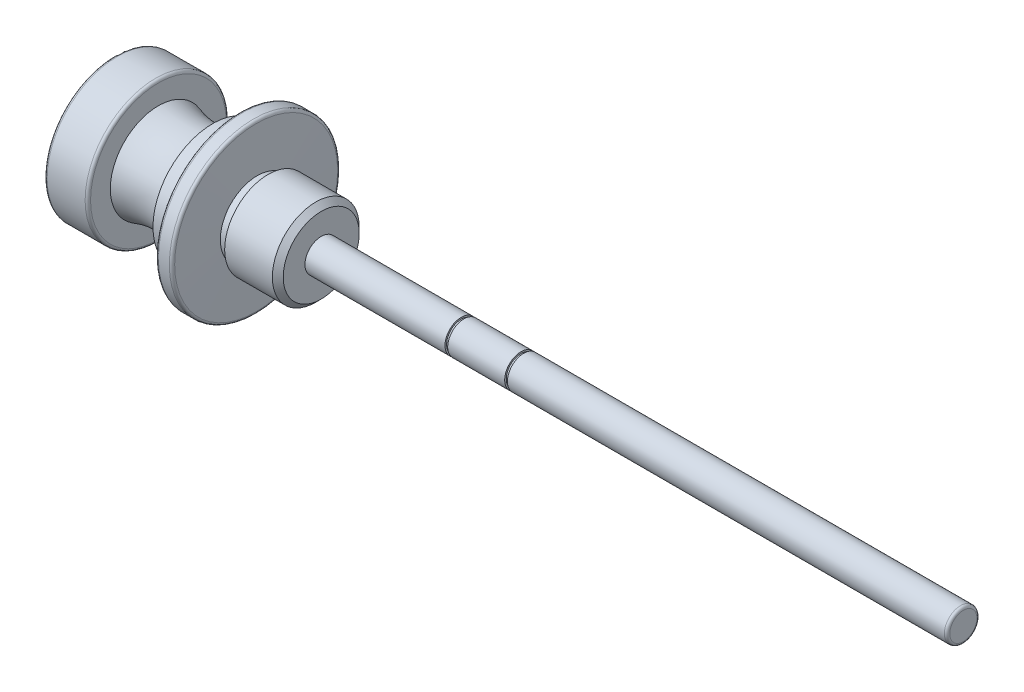
SolidWorks part; units mm, degrees
ref_plane "前视基准面" through (0, 0, 0) normal (0, 0, 1) x (1, 0, 0)
ref_plane "上视基准面" through (0, 0, 0) normal (0, 1, 0) x (1, 0, 0)
ref_plane "右视基准面" through (0, 0, 0) normal (1, 0, 0) x (0, 0, -1)
other "Configuration Table"
sketch "草图1" plane through (0, 0, 0) normal (0, 0, 1) x (1, 0, 0)
  line L0 (0, 0) -> (46.2635, 0) construction
  line L1 (0, 8.8579) -> (0, 11)
  line L2 (0, 11) -> (5, 11)
  line L3 (5, 11) -> (5, 15.5)
  line L4 (5, 15.5) -> (8, 15.5)
  line L5 (8, 15.5) -> (8.2093, 6.8)
  line L6 (8.2093, 6.8) -> (10.2093, 6.8)
  line L7 (10.2093, 6.8) -> (10.2093, 8)
  line L8 (10.2093, 8) -> (20, 8)
  line L9 (20, 8) -> (20, 3)
  line L10 (0, 0) -> (20, 0)
  line L11 (8.3007, 3) -> (138.3007, 3)
  line L12 (138.3007, 3) -> (138.3007, 0)
  line L13 (138.3007, 0) -> (20, 0)
  line L14 (0, 0) -> (-10, 0)
  line L15 (-10, 8.8579) -> (-10, 13)
  line L16 (-10, 13) -> (-18, 13)
  line L17 (-18, 13) -> (-18, 2)
  line L18 (-18, 0) -> (-10, 0)
  line L19 (-5, 0) -> (-5, 15.2334) construction
  line L20 (-18, 0) -> (-20, 0)
  arc A0 (-18, 2) -> (-20, 0) centre (-18, 0) ccw
  arc A1 (-10, 8.8579) -> (0, 8.8579) centre (-5, 23) ccw
  point P24 (-5, 8)
  dimension "D1" = 11
  dimension "D11" = 8
  dimension "D12" = 4
  dimension "D16" = 30
  dimension "D2" = 5
  dimension "D3" = 4.5
  dimension "D4" = 3
  dimension "D5" = 8
  dimension "D6" = 2
  dimension "D7" = 1.2
  dimension "D8" = 9.7907
  dimension "D9" = 3
  dimension "D10" = 130
  dimension "D13" = 8
  dimension "D14" = 10
  dimension "D15" = 13
revolve "旋转1" add sketch "草图1" angle 360 about L0
chamfer "倒角1" distance 1 angle 45 1 edges at (20, 0, 8)
thread "螺纹线1" [suppressed] pitch 0.3175 start angle 0, offset 0, length 10, pitch 0.3175, diameter 16
ref_plane "基准面1" through (10.2093, 0, -8) normal (0, -1, 0) x (0, 0, -1)
sketch "螺纹线轮廓1" plane through (10.2093, 0, -8) normal (0, -1, 0) x (0, 0, -1)
  line L0 (0, 0) -> (0, 0.3175) construction
  line L11 (0, 0) -> (0, 0.2778)
  line L12 (0, 0.2778) -> (-0.1719, 0.1786)
  line L13 (-0.1719, 0.1786) -> (-0.1719, 0.0992)
  line L15 (-0.1719, 0.0992) -> (0, 0)
  line L17 (-0.1719, 0.1389) -> (0, 0.1389) construction
  point P2 (0, 0)
  dimension "Pitch" = 0.3175
  dimension "Profile_Angle" = 60
  dimension "Profile_Land" = 0.0794
  dimension "Profile_Height" = 0.1719
ref_plane "基准面2" through (57.3007, 0, 0) normal (1, 0, 0) x (0, 0, -1)
sketch "草图2" plane through (57.3007, 0, 0) normal (1, 0, 0) x (0, 0, -1)
  circle A0 centre (0, 0) radius 3 construction
  circle A1 centre (0, 0) radius 3
  circle A2 centre (0, 0) radius 2.7
  dimension "D1" = 0.3
extrude "切除-拉伸1" cut sketch "草图2" against normal blind 0.5 contours A1 A2
ref_plane "基准面3" through (46.3007, 0, 0) normal (1, 0, 0) x (0, 0, -1)
sketch "草图3" plane through (46.3007, 0, 0) normal (1, 0, 0) x (0, 0, -1)
  circle A0 centre (0, 0) radius 3 construction
  circle A1 centre (0, 0) radius 3
  circle A2 centre (0, 0) radius 2.7
  dimension "D1" = 0.3
extrude "切除-拉伸2" cut sketch "草图3" against normal blind 0.5
fillet "圆角1" radius 0.5 5 edges at (138.3007, 0, 3) (8, 0, 15.5) (5, 0, 15.5) (-10, 0, 13) (-18, 0, 13)
thread "螺纹线2" [suppressed] pitch 0.3175 start angle 0, offset 0, length 8, pitch 0.3175, diameter 26
ref_plane "基准面4" through (-17.5, 0, -13) normal (0, -1, 0) x (0, 0, -1)
sketch "螺纹线轮廓2" plane through (-17.5, 0, -13) normal (0, -1, 0) x (0, 0, -1)
  line L0 (0, 0) -> (0, 0.3175) construction
  line L11 (0, 0) -> (0, 0.2778)
  line L12 (0, 0.2778) -> (-0.1719, 0.1786)
  line L13 (-0.1719, 0.1786) -> (-0.1719, 0.0992)
  line L15 (-0.1719, 0.0992) -> (0, 0)
  line L17 (-0.1719, 0.1389) -> (0, 0.1389) construction
  point P2 (0, 0)
  dimension "Pitch" = 0.3175
  dimension "Profile_Angle" = 60
  dimension "Profile_Land" = 0.0794
  dimension "Profile_Height" = 0.1719
